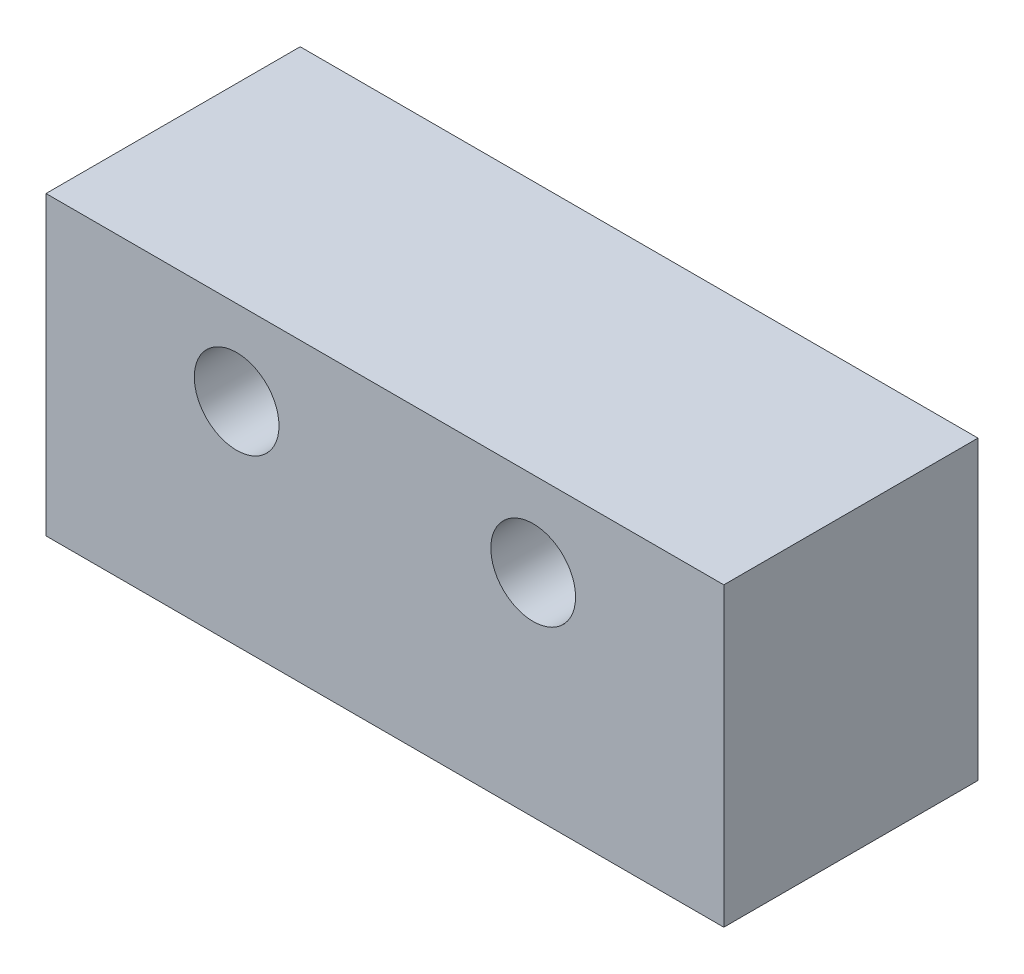
SolidWorks part; units mm, degrees
ref_plane "정면" through (0, 0, 0) normal (0, 0, 1) x (1, 0, 0)
ref_plane "윗면" through (0, 0, 0) normal (0, 1, 0) x (1, 0, 0)
ref_plane "우측면" through (0, 0, 0) normal (1, 0, 0) x (0, 0, -1)
sketch "스케치1" plane through (0, 0, 0) normal (0, 0, 1) x (1, 0, 0)
  line L1 (-8, -5) -> (8, -5)
  line L2 (-8, -5) -> (-8, 5)
  line L4 (8, -5) -> (8, 5)
  line L5 (-8, -5) -> (8, 5) construction
  line L6 (-8, 5) -> (8, -5) construction
  line L11 (-8, 5) -> (8, 5)
  point P0 (0, 0)
  dimension "D1" = 10
  dimension "D3" = 16
extrude "보스-돌출1" add sketch "스케치1" along normal mid plane 6
sketch "스케치2" plane through (0, -5, 0) normal (0, -1, 0) x (1, 0, 0)
  circle A0 centre (0, 0) radius 2
  dimension "D1" = 4
extrude "컷-돌출1" cut sketch "스케치2" against normal offset from surface (5 mm away) 5 up to face at (0, 5, 0)
sketch "스케치3" plane through (0, 0, -3) normal (0, 0, -1) x (-1, 0, 0)
  line L1 (2, 0) -> (8, 0)
  line L2 (2, 0) -> (2, 5)
  line L3 (2, 5) -> (8, 5)
  line L4 (8, 0) -> (8, 5)
  line L5 (2, 0) -> (8, 5) construction
  line L6 (2, 5) -> (8, 0) construction
  point P0 (5, 2.5)
  dimension "D1" = 6
  dimension "D2" = 5
extrude "보스-돌출2" [suppressed] add sketch "스케치3" along normal blind 5
mirror "대칭 복사1" [suppressed] about plane through (0, 0, 0) normal (0, 0, 1)
sketch "스케치4" plane through (0, 0, 3) normal (0, 0, 1) x (1, 0, 0)
  line L0 (8, -5) -> (8, 5) construction
  line L1 (-8, 5) -> (-8, -5) construction
  line L2 (-3.5, 0) -> (3.5, 0) construction
  point P3 (8, 0)
  point P6 (-8, 0)
  point P8 (0, 0)
  circle B0 centre (-3.5, 0) radius 1
  circle B1 centre (-1.25, 1.25) radius 0.65
  circle B2 centre (-1.25, -1.25) radius 0.65
  circle B3 centre (1.25, -1.25) radius 0.65
  circle B4 centre (1.25, 1.25) radius 0.65
  circle B5 centre (3.5, 0) radius 1
sketch_block_instance "블록1-1"
sketch_block "블록1"
extrude "컷-돌출2" cut sketch "스케치4" against normal blind 10
sketch "스케치5" plane through (0, 5, 0) normal (0, 1, 0) x (1, 0, 0)
  line L1 (-10.0737, -3.9963) -> (10.0737, -3.9963)
  line L2 (-10.0737, -3.9963) -> (-10.0737, 3.9963)
  line L3 (-10.0737, 3.9963) -> (10.0737, 3.9963)
  line L4 (10.0737, -3.9963) -> (10.0737, 3.9963)
  line L5 (-10.0737, -3.9963) -> (10.0737, 3.9963) construction
  line L6 (-10.0737, 3.9963) -> (10.0737, -3.9963) construction
  point P0 (0, 0)
extrude "컷-돌출3" cut sketch "스케치5" against normal blind 3
